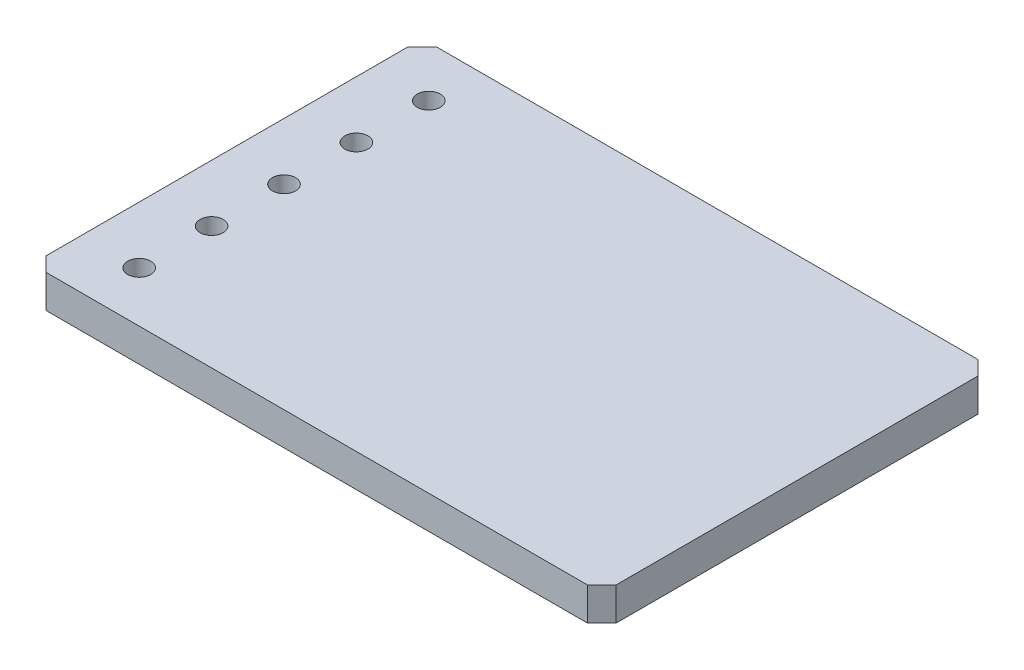
SolidWorks part; units mm, degrees
ref_plane "Front Plane" through (0, 0, 0) normal (0, 0, 1) x (1, 0, 0)
ref_plane "Top Plane" through (0, 0, 0) normal (0, 1, 0) x (1, 0, 0)
ref_plane "Right Plane" through (0, 0, 0) normal (1, 0, 0) x (0, 0, -1)
sketch "Sketch1" plane through (0, 0, 0) normal (0, 1, 0) x (1, 0, 0)
  line L1 (10, -6.85) -> (-10, -6.85)
  line L2 (10, -6.85) -> (10, 6.85)
  line L3 (10, 6.85) -> (-10, 6.85)
  line L4 (-10, -6.85) -> (-10, 6.85)
  line L5 (10, -6.85) -> (-10, 6.85) construction
  line L6 (10, 6.85) -> (-10, -6.85) construction
  circle A0 centre (-8, 0) radius 0.405
  circle A1 centre (-8, 2.54) radius 0.405
  circle A2 centre (-8, 5.08) radius 0.405
  circle A3 centre (-8, -2.54) radius 0.405
  circle A4 centre (-8, -5.08) radius 0.405
  point P1 (0, 0)
  point P8 (0, 0)
  point P14 (0, 0)
  dimension "D3" = 2
  dimension "D8" = 0.81
  dimension "D1" = 20
  dimension "D2" = 13.7
  dimension "D6" = 2.54
  dimension "D7" = 2.54
  dimension "D4" = 3
  dimension "D5" = 3
extrude "Boss-Extrude1" add sketch "Sketch1" along normal blind 1.16 contours L4 L1 L2 L3 A4 A3 A0 A1 A2
chamfer "Chamfer1" distance 0.5 angle 45 4 edges at (-10, 0.58, -6.85) (10, 0.58, -6.85) (10, 0.58, 6.85) (-10, 0.58, 6.85)
